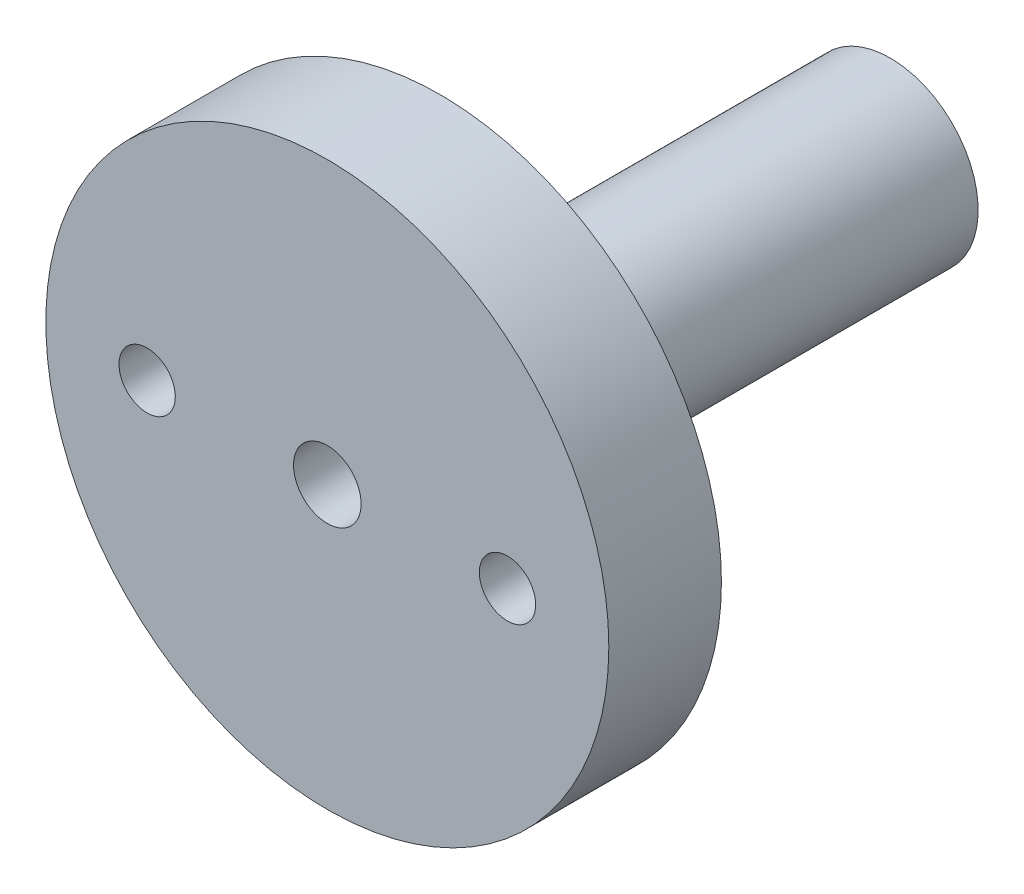
SolidWorks part; units mm, degrees
ref_plane "Front Plane" through (0, 0, 0) normal (0, 0, 1) x (1, 0, 0)
ref_plane "Top Plane" through (0, 0, 0) normal (0, 1, 0) x (1, 0, 0)
ref_plane "Right Plane" through (0, 0, 0) normal (1, 0, 0) x (0, 0, -1)
sketch "Sketch1" plane through (0, 0, 0) normal (0, 0, 1) x (1, 0, 0)
  circle A0 centre (0, 0) radius 12.5
  dimension "D1" = 25
extrude "Boss-Extrude1" add sketch "Sketch1" along normal blind 5
sketch "Sketch2" plane through (0, 0, 0) normal (0, 0, -1) x (-1, 0, 0)
  circle A0 centre (0, 0) radius 3.9
  dimension "D1" = 7.8
extrude "Boss-Extrude2" add sketch "Sketch2" along normal blind 20
sketch "Sketch3" plane through (0, 0, 5) normal (0, 0, 1) x (1, 0, 0)
  circle A0 centre (0, 0) radius 1.5
  dimension "D1" = 3
extrude "Cut-Extrude1" cut sketch "Sketch3" against normal blind 3
sketch "Sketch4" plane through (0, 0, 5) normal (0, 0, 1) x (1, 0, 0)
  circle A0 centre (8, 0) radius 1.25
  circle A1 centre (0, 0) radius 1.5 construction
  circle A2 centre (-8, 0) radius 1.25
  circle A3 centre (0, 0) radius 1.5 construction
  dimension "D1" = 2.5
  dimension "D2" = 8
  dimension "D3" = 2.5
  dimension "D4" = 8
extrude "Cut-Extrude2" cut sketch "Sketch4" against normal blind 10
